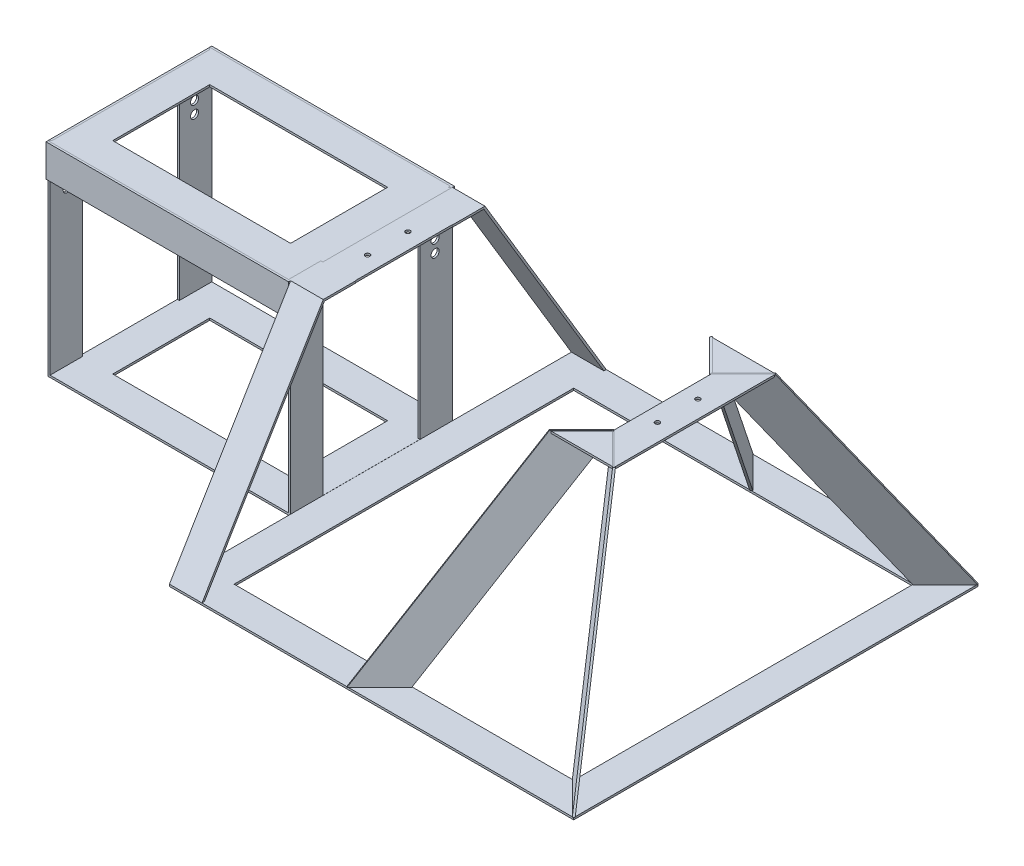
SolidWorks part; units mm, degrees
ref_plane "Front Plane" through (0, 0, 0) normal (0, 0, 1) x (1, 0, 0)
ref_plane "Top Plane" through (0, 0, 0) normal (0, 1, 0) x (1, 0, 0)
ref_plane "Right Plane" through (0, 0, 0) normal (1, 0, 0) x (0, 0, -1)
sketch "Sketch1" plane through (0, 0, 0) normal (0, 1, 0) x (1, 0, 0)
  line L0 (463.0166, 463.0166) -> (500, 500) construction
  line L1 (-500, 500) -> (500, 500)
  line L2 (-500, 500) -> (-500, -500)
  line L3 (-500, -500) -> (500, -500)
  line L4 (500, 500) -> (500, -500)
  line L5 (-500, 500) -> (-463.0166, 463.0166) construction
  line L6 (-500, -500) -> (-463.0166, -463.0166) construction
  line L12 (-420, 420) -> (420, 420)
  line L13 (463.0166, -463.0166) -> (500, -500) construction
  line L14 (-420, 420) -> (-420, -420)
  line L15 (-420, -420) -> (420, -420)
  line L16 (420, 420) -> (420, -420)
  point P0 (0, 0)
  point P6 (0, 0)
  point P11 (0, 0)
  dimension "D1" = 840
  dimension "D2" = 1000
  dimension "D3" = 1000
  dimension "D4" = 840
  dimension "D5" = 500
  dimension "D6" = 840
  dimension "D7" = 840
extrude "Boss-Extrude1" add sketch "Sketch1" along normal mid plane 5
sketch "Sketch2" plane through (0, 0, 0) normal (0, 1, 0) x (1, 0, 0)
  line L5 (-500.2805, 200) -> (299.7195, 200)
  line L6 (-500.2805, 200) -> (-500.2805, -200)
  line L7 (-500.2805, -200) -> (299.7195, -200)
  line L8 (299.7195, 200) -> (299.7195, -200)
  line L11 (420, -420) -> (420, 420) construction
  line L13 (-420.2805, 120) -> (219.7195, 120)
  line L14 (-420.2805, 120) -> (-420.2805, -120)
  line L15 (-420.2805, -120) -> (219.7195, -120)
  line L16 (219.7195, 120) -> (219.7195, -120)
  point P0 (-100.2805, 0)
  point P8 (420, 0)
  point P9 (-100.2805, 0)
  dimension "D1" = 400
  dimension "D2" = 800
  dimension "D3" = 640
  dimension "D4" = 240
extrude "Boss-Extrude2" add sketch "Sketch2" along normal mid plane 5 from offset 500 separate body
ref_plane "Plane1" through (-0.2444, 0.0488, 0.2444) normal (-0.7002, 0.1396, 0.7002) x (0.714, 0.1369, 0.6867)
sketch "Sketch5" plane through (-0.2444, 0.0488, 0.2444) normal (-0.7002, 0.1396, 0.7002) x (0.714, 0.1369, 0.6867)
  line L0 (308.0866, 469.3244) -> (420.1365, 453.6775)
  line L1 (700.654, -95.3418) -> (588.6042, -79.6949)
  line L2 (588.6042, -79.6949) -> (308.0866, 469.3244)
  line L3 (420.1365, 453.6775) -> (700.654, -95.3418)
extrude "Boss-Extrude3" add sketch "Sketch5" along normal mid plane 5
mirror "Mirror1" about plane through (0, 0, 0) normal (0, 0, 1) of "Boss-Extrude3"
ref_plane "Plane2" through (0, 221.25, 368.75) normal (0, 0.5145, 0.8575) x (1, 0, 0)
sketch "Sketch6" plane through (0, 221.25, 368.75) normal (0, 0.5145, 0.8575) x (1, 0, 0)
  line L0 (-500.2805, 327.991) -> (-419.4925, 327.991)
  line L1 (-500.2805, 327.991) -> (296.149, 327.991) construction
  line L2 (-419.4925, 327.991) -> (-419.4925, -255.1041)
  line L3 (-500, -255.1041) -> (500, -255.1041) construction
  line L4 (-419.4925, -255.1041) -> (-500, -255.1041)
  line L5 (-500, -255.1041) -> (-500.2805, 327.991)
extrude "Boss-Extrude4" add sketch "Sketch6" against normal blind 5
mirror "Mirror2" about plane through (0, 0, 0) normal (0, 0, 1) of "Boss-Extrude4"
sketch "Sketch7" plane through (0, 0, 0) normal (0, 1, 0) x (1, 0, 0)
  line L0 (-419.4925, 200) -> (-419.4925, -200)
  line L1 (-419.4925, -200) -> (218.1089, -200)
  line L2 (-419.4925, -200) -> (296.149, -200) construction
  line L3 (218.1089, -200) -> (218.1089, 200)
  line L4 (296.149, 200) -> (-419.4925, 200) construction
  line L5 (218.1089, 200) -> (-419.4925, 200)
extrude "Cut-Extrude1" cut sketch "Sketch7" along normal mid plane 5 from offset 500 contours L5 L0 L1 L3
sketch "Sketch8" plane through (0, 0, 0) normal (0, 1, 0) x (1, 0, 0)
  line L1 (-1100.2805, 200) -> (-500.2805, 200)
  line L2 (-1100.2805, 200) -> (-1100.2805, -200)
  line L3 (-1100.2805, -200) -> (-500.2805, -200)
  line L4 (-500.2805, 200) -> (-500.2805, -200)
  line L5 (-1020.2805, 120) -> (-580.2805, 120)
  line L6 (-1020.2805, 120) -> (-1020.2805, -120)
  line L7 (-1020.2805, -120) -> (-580.2805, -120)
  line L8 (-580.2805, 120) -> (-580.2805, -120)
  point P0 (-791.901, 0)
  point P6 (-791.901, 0)
  dimension "D1" = 400
  dimension "D2" = 600
  dimension "D3" = 80
  dimension "D4" = 80
  dimension "D5" = 80
  dimension "D6" = 80
extrude "Boss-Extrude5" add sketch "Sketch8" against normal blind 2.5 and the other way blind 502.5 separate body
sketch "Sketch9" plane through (-1100.2805, 0, 0) normal (-1, 0, 0) x (0, 0, 1)
  line L0 (200, 502.5) -> (200, -2.5) construction
  line L1 (-200.7814, 497.5) -> (200, 497.5)
  line L2 (-200.7814, 497.5) -> (-200.7814, 2.5)
  line L3 (-200.7814, 2.5) -> (200, 2.5)
  line L4 (200, 497.5) -> (200, 2.5)
  line L5 (-200.7814, 497.5) -> (200, 2.5) construction
  line L6 (-200.7814, 2.5) -> (200, 497.5) construction
  line L7 (-494.169, 2.5) -> (494.169, 2.5) construction
  line L8 (-200, 502.5) -> (200, 502.5) construction
  point P0 (-0.3907, 250)
  dimension "D1" = 5
extrude "Cut-Extrude5" cut sketch "Sketch9" against normal blind 600
sketch "Sketch15" plane through (0, 2.5, 0) normal (0, 1, 0) x (1, 0, 0)
  line L0 (-500.2805, -200) -> (-505.2806, -200)
  line L1 (-500.2805, -200) -> (-1100.2805, -200) construction
  line L2 (-505.2806, -200) -> (-505.2806, -120)
  line L3 (-505.2806, -120) -> (-500.2805, -120)
  line L4 (-500.2805, 200) -> (-500.2805, -200) construction
  line L5 (-500.2805, -120) -> (-500.2805, -200)
  dimension "D1" = 5.0001
  dimension "D2" = 80
extrude "Boss-Extrude8" add sketch "Sketch15" along normal blind 500
mirror "Mirror3" about plane through (0, 0, 0) normal (0, 0, 1) of "Boss-Extrude8"
ref_plane "Plane3" through (-800.2805, 0, 0) normal (-1, 0, 0) x (0, 0, 1)
mirror "Mirror4" about plane through (-800.2805, 0, 0) normal (-1, 0, 0) of "Mirror3", "Boss-Extrude8"
sketch "Sketch16" plane through (-1100.2805, 0, 0) normal (-1, 0, 0) x (0, 0, 1)
  line L0 (200, 502.5) -> (120, 502.5) construction
  line L2 (-200, 502.5) -> (-120, 502.5) construction
  line L4 (120, 502.5) -> (120, 2.5) construction
  line L5 (-120, 502.5) -> (-120, 2.5) construction
  circle A0 centre (157.5, 442.5) radius 10
  circle A1 centre (157.5, 412.5) radius 10
  circle A2 centre (157.5, 382.5) radius 10
  circle A3 centre (-157.5, 442.5) radius 10
  circle A4 centre (-157.5, 412.5) radius 10
  circle A5 centre (-157.5, 382.5) radius 10
  point P17 (0, 0)
  point P21 (0, 0)
  point P22 (0, 0)
  dimension "D1" = 3
  dimension "D4" = 20
  dimension "D7" = 20
  dimension "D2" = 60
  dimension "D3" = 30
  dimension "D5" = 30
  dimension "D6" = 37.5
  dimension "D8" = 60
  dimension "D9" = 37.5
  dimension "D10" = 30
  dimension "D11" = 315
extrude "Cut-Extrude6" cut sketch "Sketch16" against normal blind 611
sketch "Sketch17" plane through (0, 0, 0) normal (0, 0, 1) x (1, 0, 0)
  line L0 (-1100.2805, 502.5) -> (-500.2805, 502.5)
  line L1 (-500.2805, 502.5) -> (-500.2356, 422.5)
  line L2 (-500.2805, 502.5) -> (-500, 2.5) construction
  line L3 (-500.2356, 422.5) -> (-1100.2805, 422.5)
  line L4 (-1100.2805, 502.5) -> (-1100.2805, -2.5) construction
  line L5 (-1100.2805, 422.5) -> (-1100.2805, 502.5)
  dimension "D1" = 80
extrude "Boss-Extrude9" add sketch "Sketch17" along normal blind 5 from offset 200
mirror "Mirror6" about plane through (0, 0, 0) normal (0, 0, 1) of "Boss-Extrude9"
sketch "Sketch18" plane through (0, 0, -120) normal (0, 0, 1) x (1, 0, 0)
  line L0 (-1100.2805, 502.5) -> (-1095.2804, 502.5)
  line L1 (-1095.2804, 502.5) -> (-1095.2804, 422.5018)
  line L2 (-1095.2804, 502.5) -> (-1095.2804, 2.5) construction
  line L3 (-1095.2804, 422.5018) -> (-1100.2805, 422.5018)
  line L4 (-1100.2805, 502.5) -> (-1100.2805, 2.5) construction
  line L5 (-1100.2805, 422.5018) -> (-1100.2805, 502.5)
extrude "Boss-Extrude10" add sketch "Sketch18" along normal up to surface (240 mm away) up to face at (-1097.7804, 252.5, 120)
sketch "Sketch19" plane through (0, 502.5, 0) normal (0, 1, 0) x (1, 0, 0)
  line L0 (-1000, 0) -> (49000, 0) construction
  line L1 (-420, 420) -> (-420, -420) construction
  line L2 (257.1289, 200) -> (257.1289, -200) construction
  line L3 (296.149, 200) -> (218.1089, 200) construction
  line L4 (218.1089, -200) -> (296.149, -200) construction
  circle A0 centre (-460, 50) radius 5.75
  circle A1 centre (-460, -50) radius 5.75
  circle A2 centre (257.1289, 50) radius 5.75
  circle A3 centre (257.1289, -50) radius 5.75
  dimension "D1" = 11.5
  dimension "D4" = 11.5
  dimension "D2" = 50
  dimension "D3" = 40
extrude "Cut-Extrude7" cut sketch "Sketch19" against normal blind 5
ref_plane "Plane5" through (219.7195, 0, 0) normal (-1, 0, 0) x (0, 0, 1)
mirror "Mirror8" about plane through (219.7195, 0, 0) normal (-1, 0, 0) of "Boss-Extrude3"
sketch "Sketch20" plane through (218.1089, 0, 0) normal (-1, 0, 0) x (0, 0, 1)
  line L1 (200, 497.5) -> (125.1811, 497.5)
  line L2 (200, 497.5) -> (200, 502.5)
  line L3 (200, 502.5) -> (125.1811, 502.5)
  line L4 (125.1811, 497.5) -> (125.1811, 502.5)
extrude "Boss-Extrude11" add sketch "Sketch20" along normal up to body separate body
mirror "Mirror9" about plane through (0, 0, 0) normal (0, 0, 1) of "Mirror8"
sketch "Sketch21" plane through (218.1089, 0, 0) normal (-1, 0, 0) x (0, 0, 1)
  line L1 (-200, 497.5) -> (-125.1811, 497.5)
  line L2 (-200, 497.5) -> (-200, 502.5)
  line L3 (-200, 502.5) -> (-125.1811, 502.5)
  line L4 (-125.1811, 497.5) -> (-125.1811, 502.5)
extrude "Boss-Extrude12" add sketch "Sketch21" along normal up to body separate body
